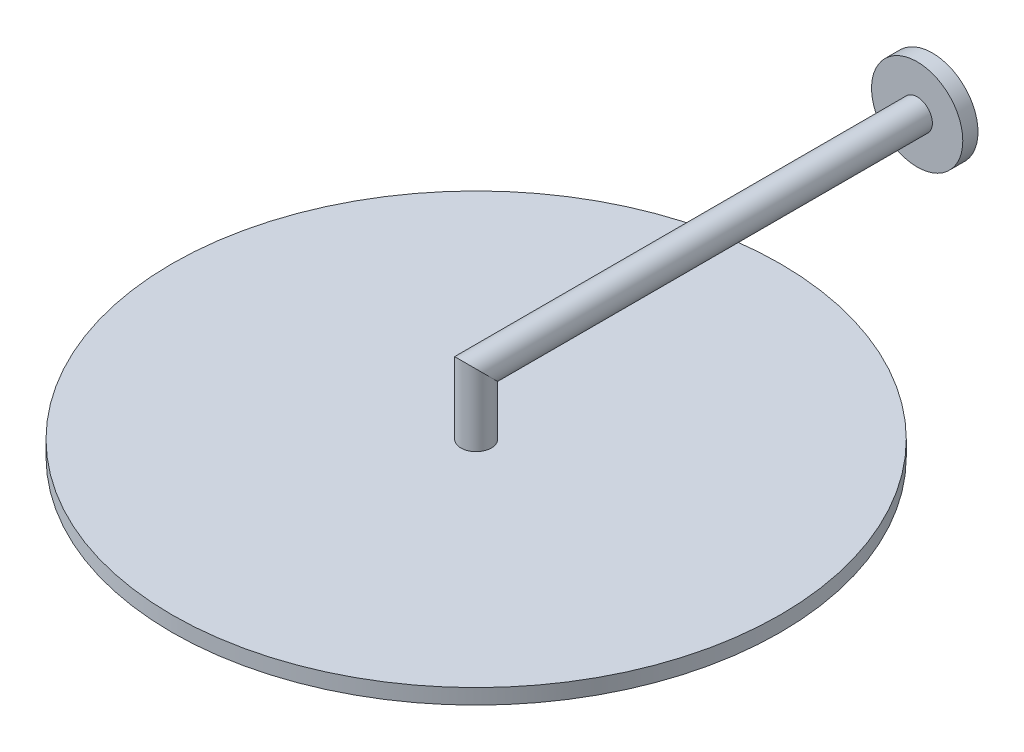
SolidWorks part; units mm, degrees
ref_plane "Спереди" through (0, 0, 0) normal (0, 0, 1) x (1, 0, 0)
ref_plane "Сверху" through (0, 0, 0) normal (0, 1, 0) x (1, 0, 0)
ref_plane "Справа" through (0, 0, 0) normal (1, 0, 0) x (0, 0, -1)
sketch "Эскиз1" plane through (0, 0, 0) normal (0, 0, 1) x (1, 0, 0)
  circle A0 centre (0, 0) radius 30
  dimension "D1" = 60
extrude "Бобышка-Вытянуть1" add sketch "Эскиз1" along normal blind 10
sketch3d "Трехмерный эскиз1"
  line L0 (0, 0, 0) -> (0, 0, 300)
  line L1 (0, 0, 300) -> (0, -40, 300)
  dimension "D1" = 300
  dimension "D2" = 40
sweep "По траектории1" add path "Трехмерный эскиз1" circular profile diameter 20 parameters "D3"=20
sketch "Эскиз7" plane through (0, -40, 0) normal (0, -1, 0) x (-1, 0, 0)
  circle A0 centre (0, -300) radius 200
  dimension "D1" = 400
extrude "Бобышка-Вытянуть2" add sketch "Эскиз7" along normal blind 10
